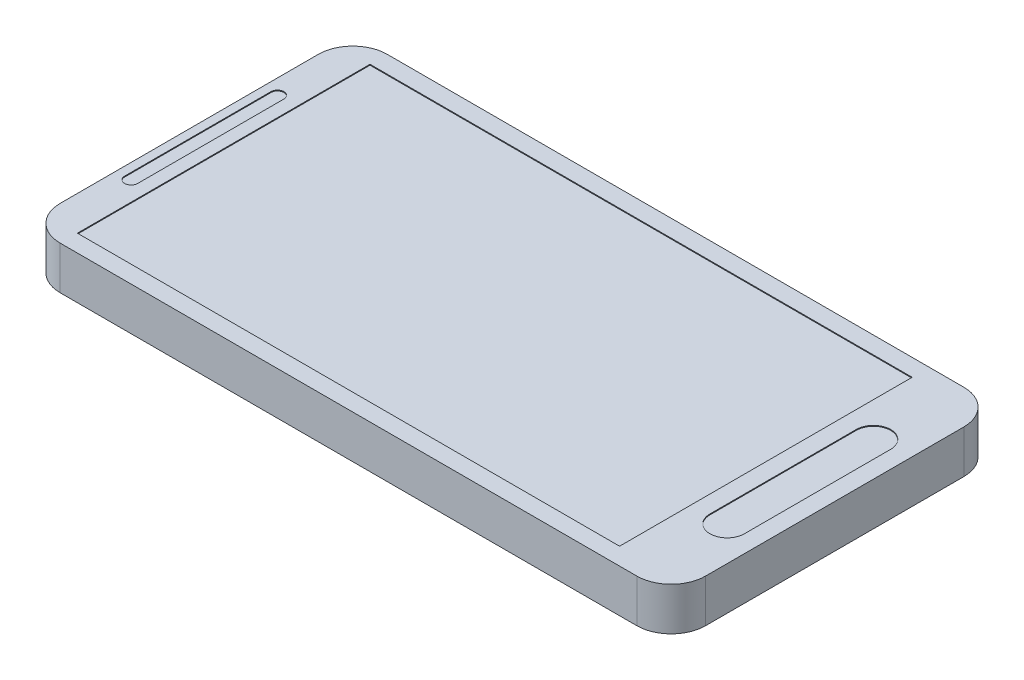
SolidWorks part; units mm, degrees
ref_plane "Front Plane" through (0, 0, 0) normal (0, 0, 1) x (1, 0, 0)
ref_plane "Top Plane" through (0, 0, 0) normal (0, 1, 0) x (1, 0, 0)
ref_plane "Right Plane" through (0, 0, 0) normal (1, 0, 0) x (0, 0, -1)
sketch "Sketch1" plane through (0, 0, 0) normal (0, 1, 0) x (1, 0, 0)
  line L1 (0, 0) -> (150, 0)
  line L2 (0, 0) -> (0, 76)
  line L3 (0, 76) -> (150, 76)
  line L4 (150, 0) -> (150, 76)
  dimension "D1" = 150
  dimension "D2" = 76
extrude "Boss-Extrude1" add sketch "Sketch1" along normal blind 10
sketch "Sketch2" plane through (0, 10, 0) normal (0, 1, 0) x (1, 0, 0)
  line L0 (8, 4) -> (134, 4)
  line L1 (134, 4) -> (134, 72)
  line L2 (134, 72) -> (8, 72)
  line L3 (8, 72) -> (8, 4)
  line L4 (150, 76) -> (0, 76) construction
  line L7 (0, 76) -> (0, 0) construction
  line L8 (0, 0) -> (150, 0) construction
  line L9 (150, 0) -> (150, 76) construction
  line L10 (134, 55) -> (150, 55) construction
  line L11 (134, 21) -> (150, 21) construction
  line L12 (142, 21) -> (142, 55) construction
  line L13 (138, 21) -> (138, 55)
  line L14 (146, 21) -> (146, 55)
  line L15 (134, 55) -> (0, 55) construction
  line L16 (134, 21) -> (0, 21) construction
  line L17 (3.5, 55) -> (3.5, 21) construction
  line L18 (5, 55) -> (5, 21)
  line L19 (2, 55) -> (2, 21)
  arc A0 (138, 21) -> (146, 21) centre (142, 21) ccw
  arc A1 (146, 55) -> (138, 55) centre (142, 55) ccw
  arc A2 (5, 55) -> (2, 55) centre (3.5, 55) ccw
  arc A3 (2, 21) -> (5, 21) centre (3.5, 21) ccw
  point P18 (142, 38)
  point P27 (3.5, 38)
  dimension "D1" = 4
  dimension "D2" = 8
  dimension "D3" = 4
  dimension "D4" = 16
  dimension "D5" = 17
  dimension "D6" = 17
  dimension "D7" = 8
  dimension "D8" = 3.5
  dimension "D9" = 3
extrude "Cut-Extrude1" cut sketch "Sketch2" against normal blind 0.2
fillet "Fillet1" radius 8 4 edges at (0, 5, 0) (0, 5, -76) (150, 5, -76) (150, 5, 0)
